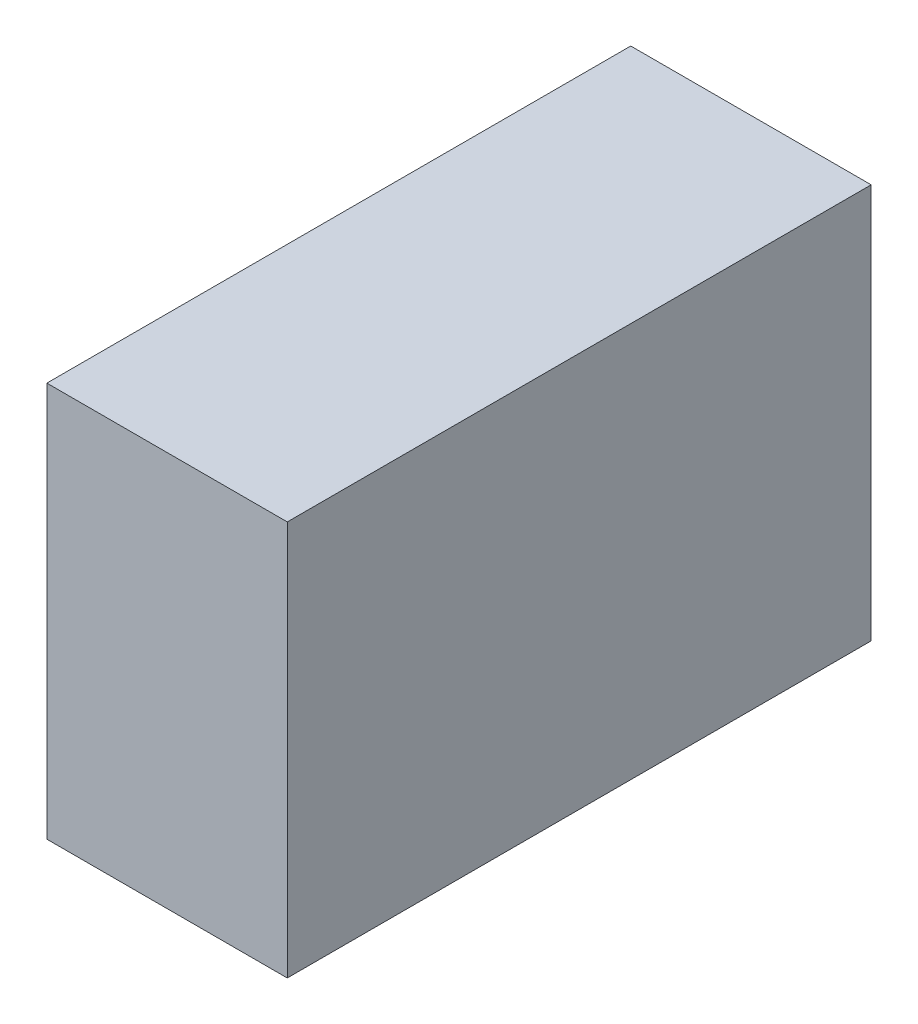
SolidWorks part; units mm, degrees
ref_plane "Front Plane" through (0, 0, 0) normal (0, 0, 1) x (1, 0, 0)
ref_plane "Top Plane" through (0, 0, 0) normal (0, 1, 0) x (1, 0, 0)
ref_plane "Right Plane" through (0, 0, 0) normal (1, 0, 0) x (0, 0, -1)
sketch "Sketch1" plane through (0, 0, 0) normal (1, 0, 0) x (0, 0, -1)
  line L1 (0, 0) -> (86.36, 0)
  line L2 (0, 0) -> (0, 58.42)
  line L3 (0, 58.42) -> (86.36, 58.42)
  line L4 (86.36, 0) -> (86.36, 58.42)
  dimension "D1" = 58.42
  dimension "D2" = 86.36
extrude "Boss-Extrude1" add sketch "Sketch1" along normal blind 35.56
